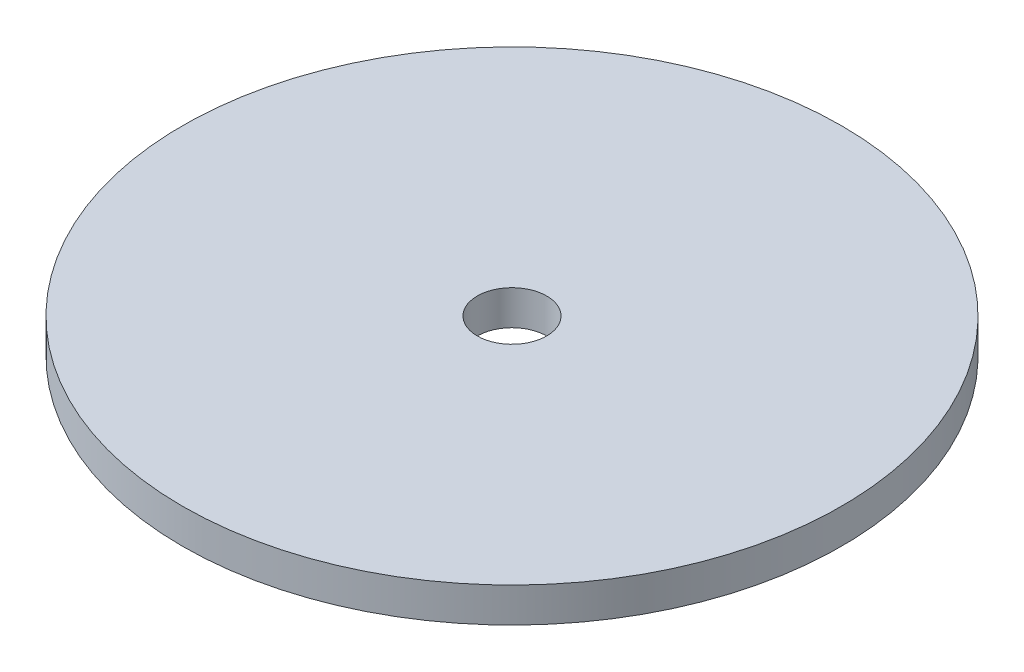
SolidWorks part; units mm, degrees
ref_plane "Front Plane" through (0, 0, 0) normal (0, 0, 1) x (1, 0, 0)
ref_plane "Top Plane" through (0, 0, 0) normal (0, 1, 0) x (1, 0, 0)
ref_plane "Right Plane" through (0, 0, 0) normal (1, 0, 0) x (0, 0, -1)
sketch "Sketch1" plane through (0, 0, 0) normal (0, 1, 0) x (1, 0, 0)
  circle A0 centre (0, 0) radius 47.5
  dimension "D1" = 95
extrude "Boss-Extrude1" add sketch "Sketch1" along normal blind 5
sketch "Sketch2" plane through (0, 5, 0) normal (0, 1, 0) x (1, 0, 0)
  circle A0 centre (0, 0) radius 5
  dimension "D1" = 10
extrude "Cut-Extrude1" cut sketch "Sketch2" against normal blind 5
